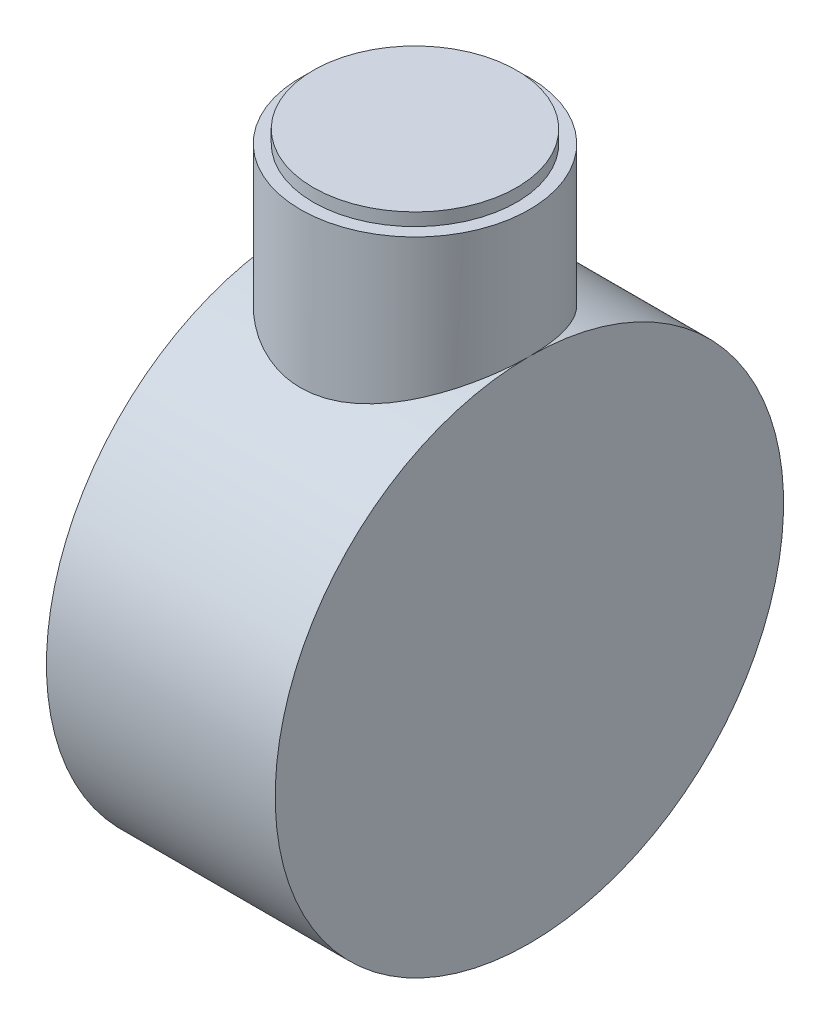
SolidWorks part; units mm, degrees
ref_plane "Front Plane" through (0, 0, 0) normal (0, 0, 1) x (1, 0, 0)
ref_plane "Top Plane" through (0, 0, 0) normal (0, 1, 0) x (1, 0, 0)
ref_plane "Right Plane" through (0, 0, 0) normal (1, 0, 0) x (0, 0, -1)
sketch "Sketch3" plane through (0, 0, 0) normal (1, 0, 0) x (0, 0, -1)
  circle A0 centre (0, 0) radius 100
  dimension "D1" = 200
extrude "Boss-Extrude1" add sketch "Sketch3" along normal blind 90
ref_plane "Plane1" through (0, 150, 0) normal (0, 1, 0) x (1, 0, 0)
sketch "Sketch4" plane through (0, 150, 0) normal (0, 1, 0) x (1, 0, 0)
  line L0 (90, -100) -> (90, 100) construction
  circle A0 centre (45, 0) radius 45
  dimension "D1" = 90
  dimension "D2" = 45
extrude "Boss-Extrude2" add sketch "Sketch4" against normal up to surface (60.6971 mm away) contours A0
sketch "Sketch5" plane through (0, 150, 0) normal (0, 1, 0) x (1, 0, 0)
  circle A0 centre (45, 0) radius 40
  dimension "D1" = 80
extrude "Boss-Extrude3" add sketch "Sketch5" along normal blind 5
